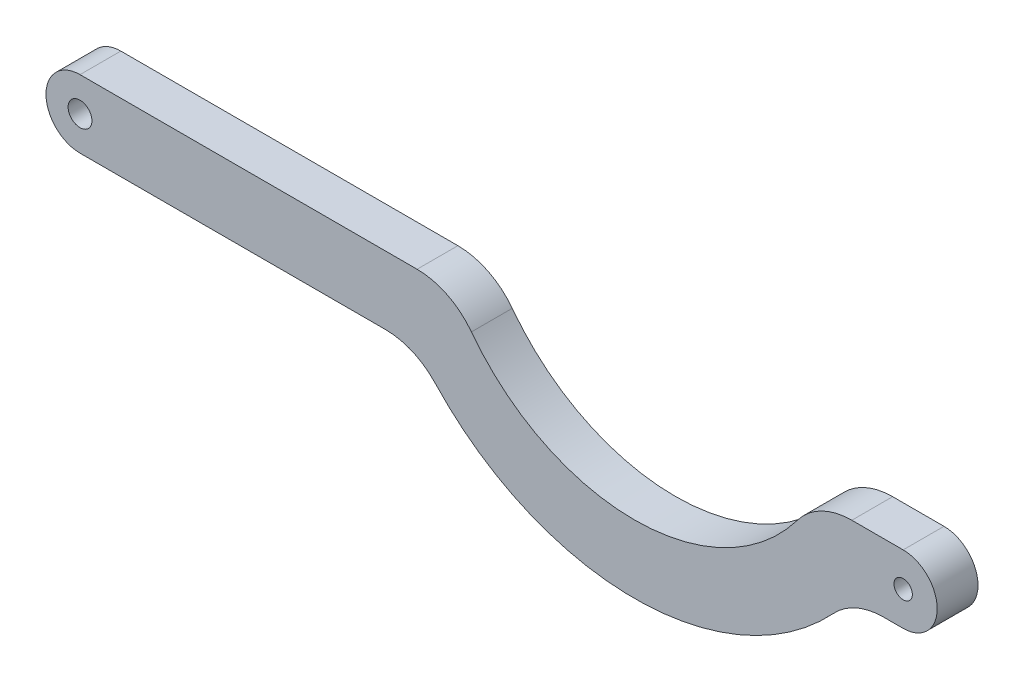
SolidWorks part; units mm, degrees
ref_plane "Plan de face" through (0, 0, 0) normal (0, 0, 1) x (1, 0, 0)
ref_plane "Plan de dessus" through (0, 0, 0) normal (0, 1, 0) x (1, 0, 0)
ref_plane "Plan de droite" through (0, 0, 0) normal (1, 0, 0) x (0, 0, -1)
sketch "Esquisse1" plane through (0, 0, 0) normal (0, 0, 1) x (1, 0, 0)
  line L0 (113.4531, 0) -> (121, 0)
  line L1 (0, 0) -> (49.5469, 0)
  line L2 (0, 0) -> (0, 10) construction
  line L3 (0, 10) -> (55, 10)
  line L4 (121, 0) -> (121, 10) construction
  line L5 (108, 10) -> (121, 10)
  arc A0 (0, 10) -> (0, 0) centre (0, 5) ccw
  arc A1 (121, 10) -> (121, 0) centre (121, 5) cw
  circle A2 centre (0, 5) radius 1.75
  circle A3 centre (121, 5) radius 1.35
  arc A4 (49.5469, 0) -> (113.4531, 0) centre (81.5, 24.0624) ccw
  arc A5 (55, 10) -> (108, 10) centre (81.5, 24.0624) ccw
  dimension "D3" = 3.5
  dimension "D5" = 10
  dimension "D6" = 30
  dimension "D8" = 2.7
  dimension "D1" = 10
  dimension "D2" = 121
  dimension "D4" = 13
  dimension "D7" = 55
extrude "Boss.-Extru.1" add sketch "Esquisse1" along normal blind 6
chamfer "Chanfrein1" distance 1.25 angle 45 1 edges at (1.75, 5, 0)
fillet "Congé1" radius 10 4 edges at (108, 10, 3) (113.4531, 0, 3) (49.5469, 0, 3) (55, 10, 3)
